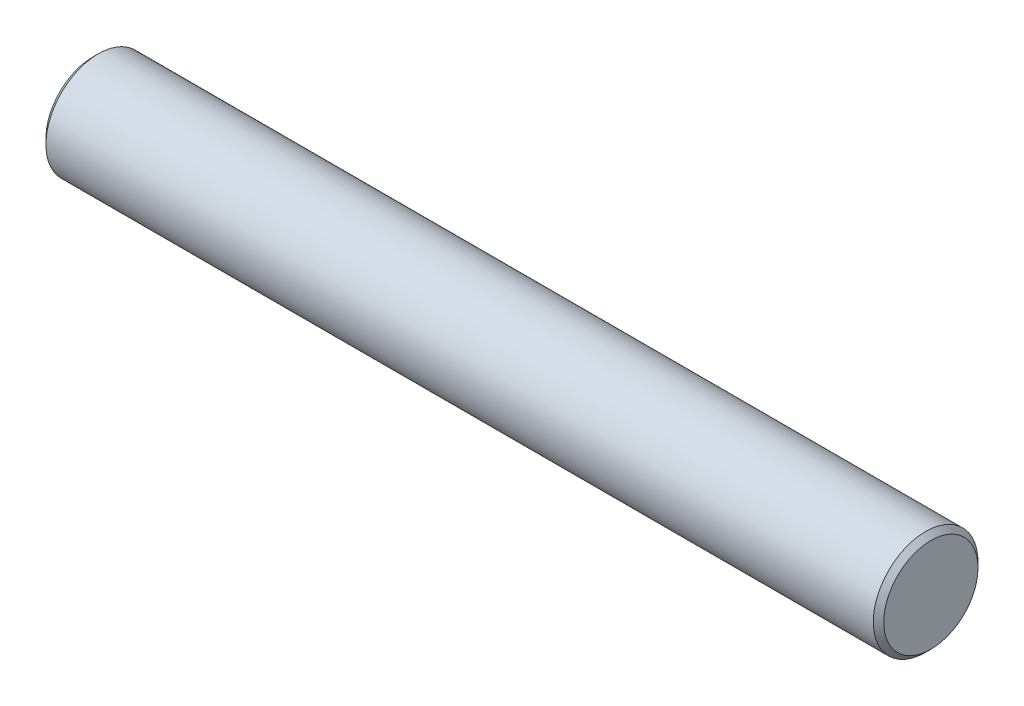
SolidWorks part; units mm, degrees
material "AISI 316 Annealed Stainless Steel Bar (SS)"
ref_plane "Front Plane" through (0, 0, 0) normal (0, 0, 1) x (1, 0, 0)
ref_plane "Top Plane" through (0, 0, 0) normal (0, 1, 0) x (1, 0, 0)
ref_plane "Right Plane" through (0, 0, 0) normal (1, 0, 0) x (0, 0, -1)
sketch "Sketch1" plane through (0, 0, 0) normal (1, 0, 0) x (0, 0, -1)
  circle A0 centre (0, 0) radius 2.5
  dimension "D1" = 5
extrude "Boss-Extrude1" add sketch "Sketch1" along normal mid plane 40
chamfer "Chamfer1" distance 0.25 angle 45 2 edges at (-20, 0, -2.5) (20, 0, -2.5)
